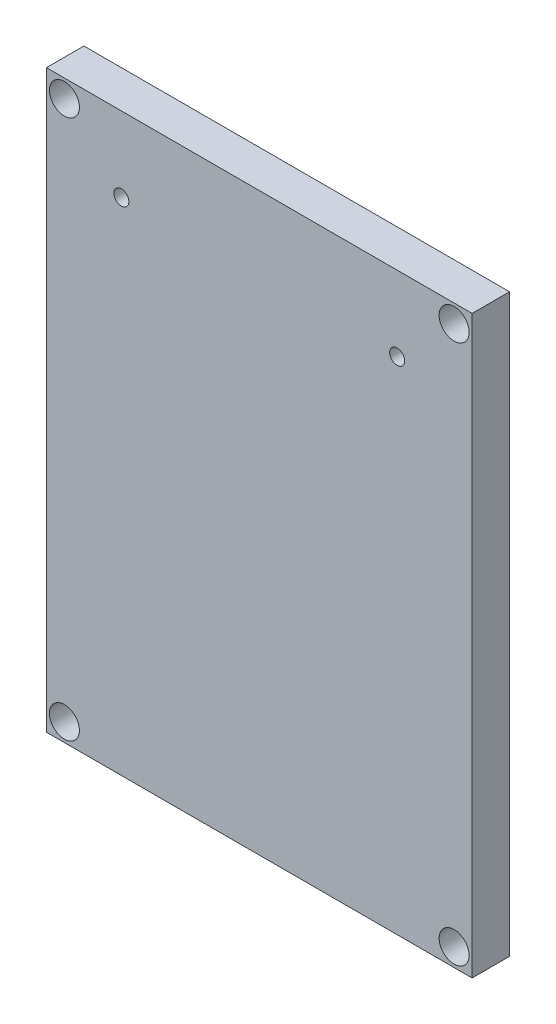
SolidWorks part; units mm, degrees
ref_plane "Front Plane" through (0, 0, 0) normal (0, 0, 1) x (1, 0, 0)
ref_plane "Top Plane" through (0, 0, 0) normal (0, 1, 0) x (1, 0, 0)
ref_plane "Right Plane" through (0, 0, 0) normal (1, 0, 0) x (0, 0, -1)
sketch "Sketch1" plane through (0, 0, 0) normal (0, 0, 1) x (1, 0, 0)
  line L1 (0, 0) -> (72.136, 0)
  line L2 (0, 0) -> (0, -97.536)
  line L3 (0, -97.536) -> (72.136, -97.536)
  line L4 (72.136, 0) -> (72.136, -97.536)
  dimension "D1" = 72.136
  dimension "D2" = 97.536
extrude "Boss-Extrude1" add sketch "Sketch1" along normal blind 6.35
sketch "Sketch12" plane through (0, 0, 6.35) normal (0, 0, 1) x (1, 0, 0)
  line L0 (0, 0) -> (0, -97.536) construction
  line L1 (72.136, 0) -> (0, 0) construction
  line L2 (72.136, -97.536) -> (72.136, 0) construction
  line L3 (0, -97.536) -> (72.136, -97.536) construction
  circle A0 centre (3.048, -3.048) radius 2.54
  circle A1 centre (69.088, -3.048) radius 2.54
  circle A2 centre (69.088, -94.488) radius 2.54
  circle A3 centre (3.048, -94.488) radius 2.54
  point P14 (0, 0)
  point P16 (70.013, -0.3498)
  point P18 (0, 0)
  point P20 (-7.5858, -82.3241)
  point P21 (0, 0)
  dimension "D1" = 5.08
  dimension "D2" = 5.08
  dimension "D3" = 5.08
  dimension "D4" = 5.08
  dimension "D5" = 3.048
  dimension "D6" = 3.048
  dimension "D7" = 3.048
  dimension "D8" = 3.048
  dimension "D9" = 3.048
  dimension "D10" = 3.048
  dimension "D11" = 3.048
  dimension "D12" = 3.048
extrude "Cut-Extrude4" cut sketch "Sketch12" against normal up to next
sketch "Sketch13" plane through (0, 0, 6.35) normal (0, 0, 1) x (1, 0, 0)
  line L0 (72.136, 0) -> (0, 0) construction
  line L1 (0, 0) -> (0, -97.536) construction
  line L2 (72.136, -97.536) -> (72.136, 0) construction
  circle A0 centre (12.7, -12.7) radius 1.27
  circle A1 centre (59.436, -12.7) radius 1.27
  dimension "D1" = 2.54
  dimension "D2" = 2.54
  dimension "D3" = 12.7
  dimension "D4" = 12.7
  dimension "D5" = 12.7
  dimension "D6" = 12.7
extrude "Cut-Extrude5" cut sketch "Sketch13" against normal blind 3.81
